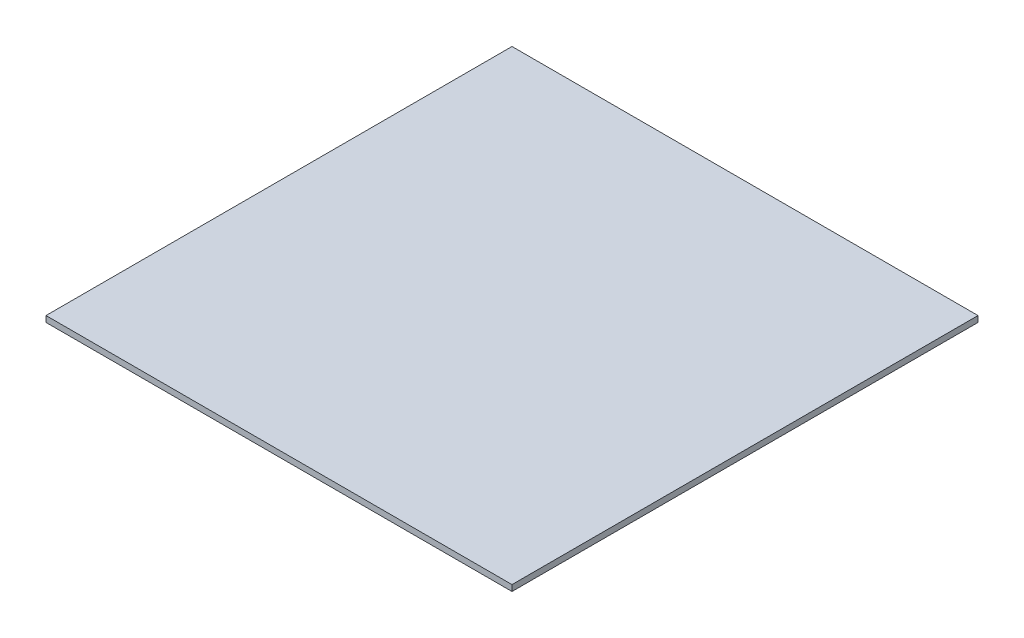
SolidWorks part; units mm, degrees
ref_plane "Front Plane" through (0, 0, 0) normal (0, 0, 1) x (1, 0, 0)
ref_plane "Top Plane" through (0, 0, 0) normal (0, 1, 0) x (1, 0, 0)
ref_plane "Right Plane" through (0, 0, 0) normal (1, 0, 0) x (0, 0, -1)
sketch "Sketch1" plane through (0, 0, 0) normal (0, 1, 0) x (1, 0, 0)
  line L1 (-155, 155) -> (155, 155)
  line L2 (-155, 155) -> (-155, -155)
  line L3 (-155, -155) -> (155, -155)
  line L4 (155, 155) -> (155, -155)
  line L5 (-155, 155) -> (155, -155) construction
  line L6 (-155, -155) -> (155, 155) construction
  point P0 (0, 0)
  dimension "D1" = 310
  dimension "D2" = 310
extrude "Boss-Extrude1" add sketch "Sketch1" along normal blind 4
